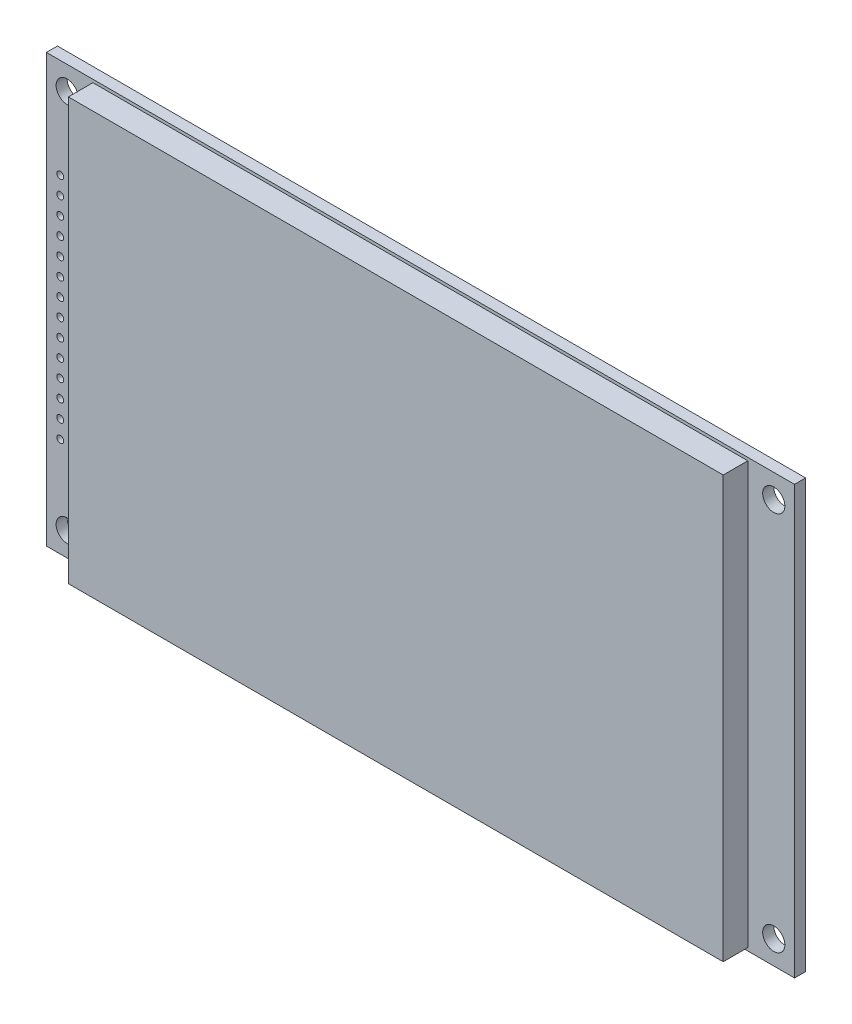
SolidWorks part; units mm, degrees
ref_plane "Front Plane" through (0, 0, 0) normal (0, 0, 1) x (1, 0, 0)
ref_plane "Top Plane" through (0, 0, 0) normal (0, 1, 0) x (1, 0, 0)
ref_plane "Right Plane" through (0, 0, 0) normal (1, 0, 0) x (0, 0, -1)
sketch "Sketch1" plane through (0, 0, 0) normal (0, 0, 1) x (1, 0, 0)
  line L1 (-54.02, 30.87) -> (54.02, 30.87)
  line L2 (-54.02, 30.87) -> (-54.02, -30.87)
  line L3 (-54.02, -30.87) -> (54.02, -30.87)
  line L4 (54.02, 30.87) -> (54.02, -30.87)
  line L5 (-54.02, 30.87) -> (54.02, -30.87) construction
  line L6 (-54.02, -30.87) -> (54.02, 30.87) construction
  circle A0 centre (-51.02, 27.45) radius 1.6
  circle A1 centre (-51.02, -27.45) radius 1.6
  circle A2 centre (51.02, -27.45) radius 1.6
  circle A3 centre (51.02, 27.45) radius 1.6
  point P0 (0, 0)
  dimension "D5" = 3.2
  dimension "D6" = 3.2
  dimension "D9" = 3.2
  dimension "D1" = 61.74
  dimension "D2" = 108.04
  dimension "D3" = 3.42
  dimension "D4" = 3
  dimension "D7" = 3
  dimension "D8" = 3.42
  dimension "D10" = 3
  dimension "D11" = 3.42
  dimension "D12" = 3
  dimension "D13" = 3.42
extrude "Boss-Extrude1" add sketch "Sketch1" along normal blind 1.6
sketch "Sketch2" plane through (0, 0, 1.6) normal (0, 0, 1) x (1, 0, 0)
  line L0 (-47.3, 0) -> (47.27, 0) construction
  line L1 (47.27, 30.44) -> (-47.3, 30.44)
  line L2 (47.27, 30.44) -> (47.27, -30.44)
  line L3 (47.27, -30.44) -> (-47.3, -30.44)
  line L4 (-47.3, 30.44) -> (-47.3, -30.44)
  line L5 (-54.02, 30.87) -> (-54.02, -30.87) construction
  dimension "D1" = 94.57
  dimension "D2" = 60.88
  dimension "D3" = 6.75
  dimension "D4" = 6.72
extrude "Boss-Extrude2" add sketch "Sketch2" along normal blind 3.55
sketch "Sketch3" plane through (0, 0, 1.6) normal (0, 0, 1) x (1, 0, 0)
  line L0 (54.02, 30.87) -> (-54.02, 30.87) construction
  circle A0 centre (-52.02, 16.51) radius 0.5
  circle A1 centre (-52.02, 13.97) radius 0.5
  circle A2 centre (-52.02, 11.43) radius 0.5
  circle A3 centre (-52.02, 8.89) radius 0.5
  circle A4 centre (-52.02, 6.35) radius 0.5
  circle A5 centre (-52.02, 3.81) radius 0.5
  circle A6 centre (-52.02, 1.27) radius 0.5
  circle A7 centre (-52.02, -1.27) radius 0.5
  circle A8 centre (-52.02, -3.81) radius 0.5
  circle A9 centre (-52.02, -6.35) radius 0.5
  circle A10 centre (-52.02, -8.89) radius 0.5
  circle A11 centre (-52.02, -11.43) radius 0.5
  circle A12 centre (-52.02, -13.97) radius 0.5
  circle A13 centre (-52.02, -16.51) radius 0.5
  dimension "D3" = 1
  dimension "D1" = 14.36
  dimension "D2" = 2
  dimension "D4" = 14
extrude "Cut-Extrude1" cut sketch "Sketch3" against normal blind 3.55
sketch "Sketch4" plane through (0, 0, 0) normal (0, 0, -1) x (-1, 0, 0)
  line L4 (-54.02, 30.87) -> (-54.02, -30.87)
  line L5 (-54.02, -30.87) -> (54.02, -30.87)
  line L6 (54.02, -30.87) -> (54.02, 30.87)
  line L7 (54.02, 30.87) -> (-54.02, 30.87)
  line L8 (-54.02, 30.87) -> (-54.02, -30.87)
  line L9 (-54.02, -30.87) -> (54.02, -30.87)
  line L10 (54.02, -30.87) -> (54.02, 30.87)
  line L11 (54.02, 30.87) -> (-54.02, 30.87)
  line L13 (51.02, 17.51) -> (53.02, 17.51)
  line L14 (51.02, 17.51) -> (51.02, -17.51)
  line L15 (51.02, -17.51) -> (53.02, -17.51)
  line L16 (53.02, 17.51) -> (53.02, -17.51)
  circle A0 centre (52.02, -16.51) radius 0.5 construction
  circle A1 centre (52.02, -16.51) radius 0.5
  circle A2 centre (52.02, 16.51) radius 0.5 construction
  circle A3 centre (52.02, 16.51) radius 0.5
  circle M9 centre (52.02, 16.51) radius 0.5
  circle M10 centre (52.02, 13.97) radius 0.5
  circle M11 centre (52.02, 11.43) radius 0.5
  circle M12 centre (52.02, 8.89) radius 0.5
  circle M13 centre (52.02, 6.35) radius 0.5
  circle M14 centre (52.02, 3.81) radius 0.5
  circle M15 centre (52.02, 1.27) radius 0.5
  circle M16 centre (52.02, -1.27) radius 0.5
  circle M17 centre (52.02, -3.81) radius 0.5
  circle M18 centre (52.02, -6.35) radius 0.5
  circle M19 centre (52.02, -8.89) radius 0.5
  circle M20 centre (52.02, -11.43) radius 0.5
  circle M21 centre (52.02, -13.97) radius 0.5
  circle M22 centre (52.02, -16.51) radius 0.5
  dimension "D2" = 1
  dimension "D3" = 1
  dimension "D4" = 1
  dimension "D5" = 1
  dimension "D1" = 0
extrude "Boss-Extrude3" add sketch "Sketch4" along normal blind 2.5 contours L16 L13 L14 L15 M10 M12 M14 M16 M18 M20 M22 M21 M19 M17 M15 M13 M11 M9
sketch "Sketch5" plane through (0, 0, -2.5) normal (0, 0, -1) x (-1, 0, 0)
  circle A0 centre (52.02, -16.51) radius 0.5 construction
  circle A1 centre (52.02, -13.97) radius 0.5 construction
  circle A2 centre (52.02, -11.43) radius 0.5 construction
  circle A3 centre (52.02, -8.89) radius 0.5 construction
  circle A4 centre (52.02, -6.35) radius 0.5 construction
  circle A5 centre (52.02, -3.81) radius 0.5 construction
  circle A6 centre (52.02, -1.27) radius 0.5 construction
  circle A7 centre (52.02, 1.27) radius 0.5 construction
  circle A8 centre (52.02, 3.81) radius 0.5 construction
  circle A9 centre (52.02, 6.35) radius 0.5 construction
  circle A10 centre (52.02, 8.89) radius 0.5 construction
  circle A11 centre (52.02, 11.43) radius 0.5 construction
  circle A12 centre (52.02, 13.97) radius 0.5 construction
  circle A13 centre (52.02, 16.51) radius 0.5 construction
  circle A14 centre (52.02, -16.51) radius 0.5
  circle A15 centre (52.02, -13.97) radius 0.5
  circle A16 centre (52.02, -11.43) radius 0.5
  circle A17 centre (52.02, -8.89) radius 0.5
  circle A18 centre (52.02, -6.35) radius 0.5
  circle A19 centre (52.02, -3.81) radius 0.5
  circle A20 centre (52.02, -1.27) radius 0.5
  circle A21 centre (52.02, 1.27) radius 0.5
  circle A22 centre (52.02, 3.81) radius 0.5
  circle A23 centre (52.02, 6.35) radius 0.5
  circle A24 centre (52.02, 8.89) radius 0.5
  circle A25 centre (52.02, 11.43) radius 0.5
  circle A26 centre (52.02, 13.97) radius 0.5
  circle A27 centre (52.02, 16.51) radius 0.5
extrude "Boss-Extrude4" add sketch "Sketch5" along normal blind 5.84 separate body
